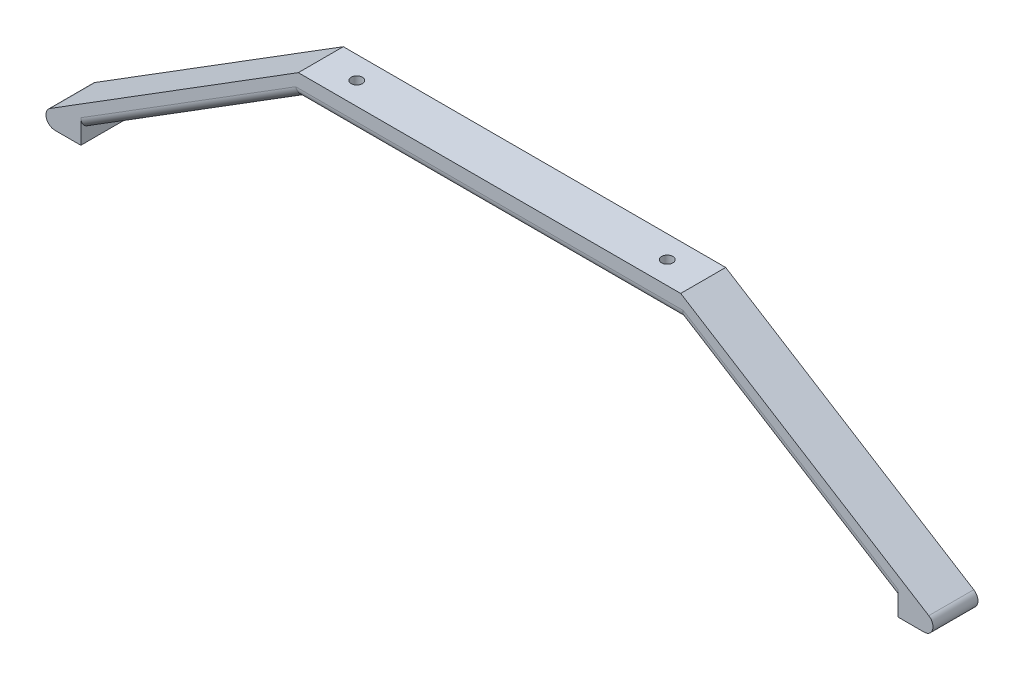
SolidWorks part; units mm, degrees
ref_plane "Plan de face" through (0, 0, 0) normal (0, 0, 1) x (1, 0, 0)
ref_plane "Plan de dessus" through (0, 0, 0) normal (0, 1, 0) x (1, 0, 0)
ref_plane "Plan de droite" through (0, 0, 0) normal (1, 0, 0) x (0, 0, -1)
sketch "Esquisse2" plane through (0, 0, 0) normal (0, 0, 1) x (1, 0, 0)
  line L0 (0, 0) -> (85, 0)
  line L1 (0, -5) -> (85, -5)
  line L2 (85, 0) -> (146.0595, -38.1542)
  line L3 (85, -5) -> (133.3387, -35.2054)
  line L4 (133.3387, -35.2054) -> (133.3387, -38.1542)
  line L5 (133.3387, -38.1542) -> (146.0595, -38.1542)
  line L6 (0, 0) -> (-61.0595, -38.1542)
  line L7 (0, -5) -> (-48.3387, -35.2054)
  line L8 (-61.0595, -38.1542) -> (-48.3387, -38.1542)
  line L9 (-48.3387, -38.1542) -> (-48.3387, -35.2054)
  dimension "D1" = 85
  dimension "D2" = 212
  dimension "D3" = 212
  dimension "D4" = 212
  dimension "D5" = 72
  dimension "D6" = 57
  dimension "D7" = 57
  dimension "D8" = 72
extrude "Boss.-Extru.2" add sketch "Esquisse2" along normal blind 10
sketch "Esquisse3" plane through (0, 0, 0) normal (0, 1, 0) x (1, 0, 0)
  line L0 (85, -10) -> (85, 0) construction
  line L1 (85, -10) -> (0, -10) construction
  line L2 (0, -10) -> (0, 0) construction
  circle A0 centre (77, -5) radius 1.25
  circle A1 centre (8, -5) radius 1.25
  point P2 (85, -5)
  dimension "D2" = 2.5
  dimension "D5" = 2.5
  dimension "D1" = 8
  dimension "D3" = 5
  dimension "D4" = 8
extrude "Enlèv. mat.-Extru.1" cut sketch "Esquisse3" against normal blind 10
fillet "Congé1" radius 2 1 edges at (42.5, -5, 10)
fillet "Congé2" radius 2 5 edges at (107.569, -19.1027, 10) (109.1694, -20.1027, 0) (-22.569, -19.1027, 10) (-24.1694, -20.1027, 0) (42.5, -5, 0)
fillet "Congé3" radius 2 1 edges at (-61.0595, -38.1542, 5)
fillet "Congé4" radius 2 1 edges at (146.0595, -38.1542, 5)
